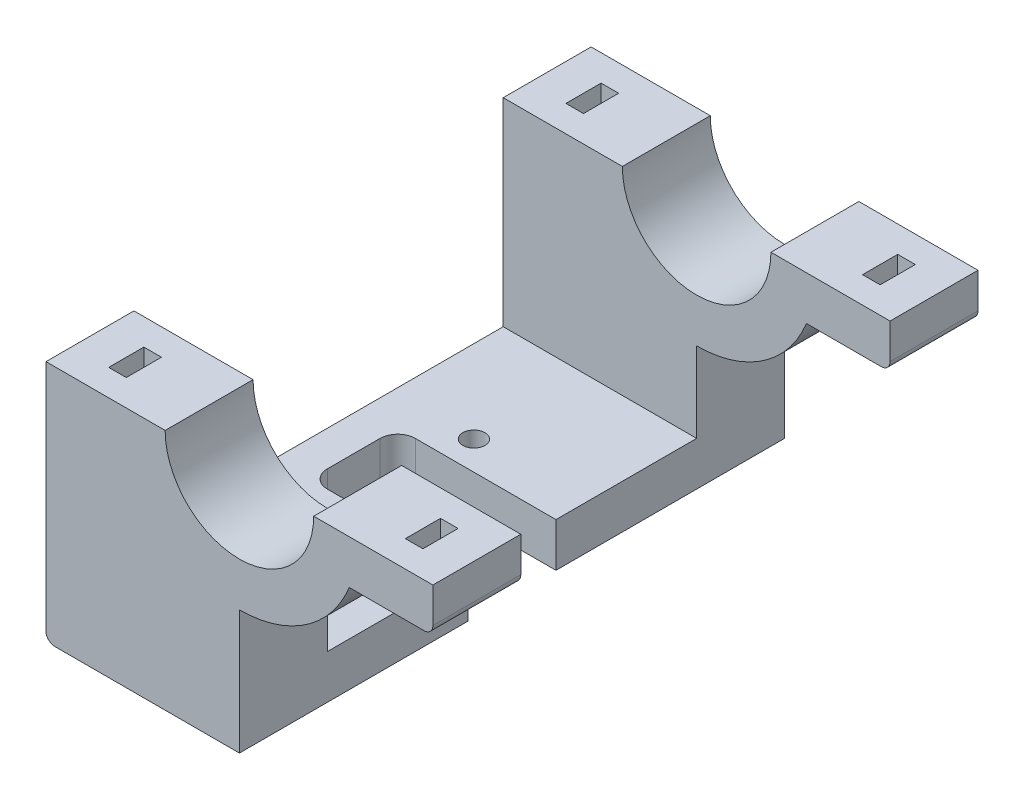
SolidWorks part; units mm, degrees
ref_plane "Front Plane" through (0, 0, 0) normal (0, 0, 1) x (1, 0, 0)
ref_plane "Top Plane" through (0, 0, 0) normal (0, 1, 0) x (1, 0, 0)
ref_plane "Right Plane" through (0, 0, 0) normal (1, 0, 0) x (0, 0, -1)
sketch "Sketch2" plane through (0, 0, 0) normal (0, 0, 1) x (1, 0, 0)
  line L0 (-27.94, 0) -> (-10.7315, 0)
  line L1 (-27.94, 0) -> (-27.94, -35)
  line L2 (-27.94, -35) -> (27.94, -35)
  line L3 (27.94, -35) -> (27.94, 0)
  line L4 (10.7315, 0) -> (27.94, 0)
  line L5 (0, 0) -> (10.7315, 0) construction
  arc A0 (-10.7315, 0) -> (10.7315, 0) centre (0, 0) ccw
  point P6 (0, 0)
  dimension "D1" = 21.463
  dimension "D2" = 55.88
  dimension "D3" = 35
  dimension "D4" = 27.94
extrude "Boss-Extrude1" add sketch "Sketch2" along normal blind 12.7
sketch "Sketch3" plane through (0, 0, 0) normal (0, 1, 0) x (1, 0, 0)
  line L0 (-27.94, -6.35) -> (27.94, -6.35) construction
  line L2 (-27.94, -12.7) -> (-27.94, 0) construction
  line L3 (-22.6931, -8.89) -> (-20.1531, -8.89)
  line L4 (27.94, -12.7) -> (27.94, 0) construction
  line L5 (-22.6931, -8.89) -> (-22.6931, -3.81)
  line L6 (-22.6931, -3.81) -> (-20.1531, -3.81)
  line L7 (-20.1531, -8.89) -> (-20.1531, -3.81)
  line L8 (-22.6931, -8.89) -> (-20.1531, -3.81) construction
  line L9 (-22.6931, -3.81) -> (-20.1531, -8.89) construction
  line L10 (22.6931, -8.89) -> (20.1531, -8.89)
  line L11 (22.6931, -8.89) -> (22.6931, -3.81)
  line L12 (22.6931, -3.81) -> (20.1531, -3.81)
  line L13 (20.1531, -8.89) -> (20.1531, -3.81)
  line L14 (22.6931, -8.89) -> (20.1531, -3.81) construction
  line L15 (22.6931, -3.81) -> (20.1531, -8.89) construction
  point P0 (-21.4231, -6.35)
  point P10 (21.4231, -6.35)
  dimension "D1" = 42.8462
  dimension "D2" = 21.4231
  dimension "D3" = 2.54
  dimension "D4" = 5.08
extrude "Cut-Extrude1" cut sketch "Sketch3" against normal through all
sketch "Sketch4" plane through (0, 0, 12.7) normal (0, 0, 1) x (1, 0, 0)
  line L0 (27.94, -35) -> (27.94, 0) construction
  line L1 (-27.94, -35) -> (27.94, -35)
  line L2 (-27.94, -35) -> (-27.94, -28.65)
  line L3 (-27.94, -28.65) -> (27.94, -28.65)
  line L4 (27.94, -35) -> (27.94, -28.65)
  dimension "D1" = 6.35
extrude "Boss-Extrude2" add sketch "Sketch4" along normal blind 26.67
ref_plane "Plane1" through (0, 0, 39.37) normal (0, 0, 1) x (1, 0, 0)
mirror "Mirror1" about plane through (0, 0, 39.37) normal (0, 0, -1) of bodies 103
sketch "Sketch5" plane through (0, -28.65, 0) normal (0, 1, 0) x (1, 0, 0)
  line L0 (-27.94, -39.37) -> (27.94, -39.37) construction
  line L3 (-22.86, -33.02) -> (8.89, -33.02)
  line L5 (-22.86, -45.7195) -> (8.89, -45.7195)
  line L9 (-27.94, -66.04) -> (-27.94, -12.7) construction
  line L10 (27.94, -66.04) -> (27.94, -12.7) construction
  line L11 (-27.94, -60.8397) -> (-27.94, -33.02) construction
  line L14 (-16.002, -49.87) -> (-16.002, -28.87) construction
  line L15 (0, -12.7) -> (0, -66.04) construction
  line L16 (27.94, -12.7) -> (-27.94, -12.7) construction
  line L17 (10.7315, -66.04) -> (-10.7315, -66.04) construction
  line L18 (8.89, -33.02) -> (8.89, -45.7195)
  line L19 (-22.86, -33.02) -> (-22.86, -45.7195)
  circle A1 centre (-16.002, -28.87) radius 1.6
  circle A2 centre (-16.002, -49.87) radius 1.6
  dimension "D9" = 3.2
  dimension "D2" = 6.35
  dimension "D3" = 12.6995
  dimension "D4" = 31.75
  dimension "D5" = 5.08
  dimension "D10" = 21
  dimension "D11" = 10.5
  dimension "D12" = 16.002
extrude "Cut-Extrude3" cut sketch "Sketch5" against normal through all
sketch "Sketch7" plane through (0, 0, 78.74) normal (0, 0, 1) x (1, 0, 0)
  line L1 (0, -17.0815) -> (0, -35)
  line L2 (15.8573, -6.35) -> (27.94, -6.35)
  line L3 (15.8573, -6.35) -> (27.94, -6.35)
  line L4 (-27.94, -35) -> (27.94, -35) construction
  line L5 (27.94, -6.35) -> (27.94, -35)
  line L6 (27.94, -35) -> (0, -35)
  arc A3 (-17.0815, 0) -> (15.8573, -6.35) centre (0, 0) ccw
  arc A4 (0, -17.0815) -> (15.8573, -6.35) centre (0, 0) ccw
  dimension "D1" = 6.35
extrude "Cut-Extrude4" cut sketch "Sketch7" against normal up to surface (78.74 mm away) up to face at (0, -13.4553, 0)
fillet "Fillet1" radius 1.27 7 edges at (-22.6931, -35, 72.39) (-27.94, -35, 39.37) (-22.6931, -35, 6.35) (22.6931, -6.35, 6.35) (27.94, -6.35, 6.35) (27.94, -6.35, 72.39) (22.6931, -6.35, 72.39)
fillet "Fillet2" radius 2.54 2 edges at (-22.86, -31.825, 45.7195) (-22.86, -31.825, 33.02)
